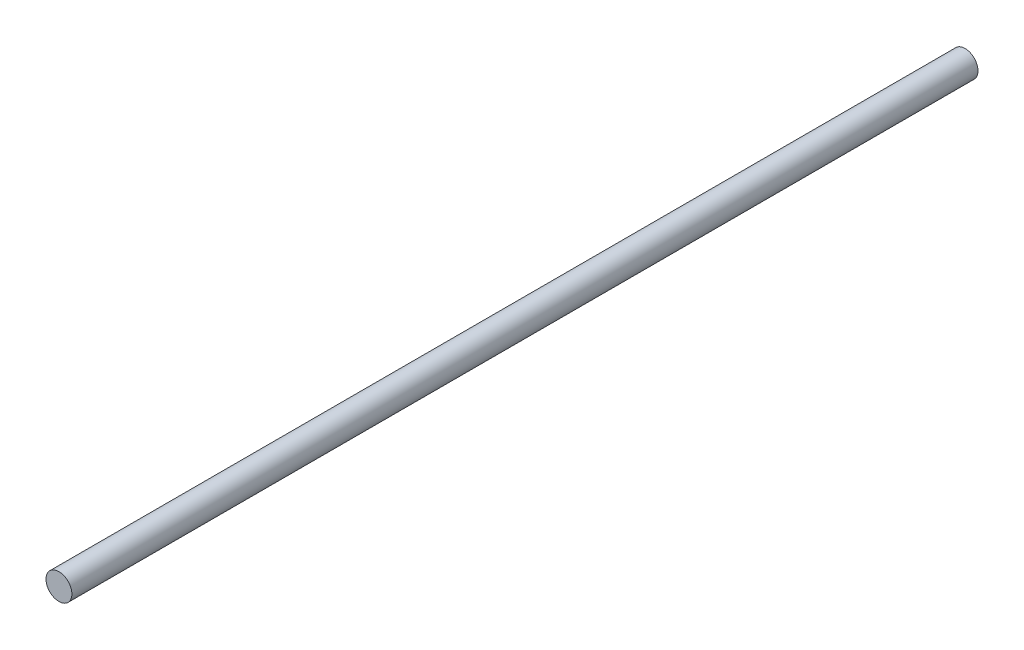
SolidWorks part; units mm, degrees
ref_plane "前基準面" through (0, 0, 0) normal (0, 0, 1) x (1, 0, 0)
ref_plane "上基準面" through (0, 0, 0) normal (0, 1, 0) x (1, 0, 0)
ref_plane "右基準面" through (0, 0, 0) normal (1, 0, 0) x (0, 0, -1)
sketch "草圖1" plane through (0, 0, 0) normal (0, 0, 1) x (1, 0, 0)
  circle A0 centre (0, 0) radius 4
  dimension "D1" = 8
extrude "填料-伸長1" add sketch "草圖1" along normal blind 280
